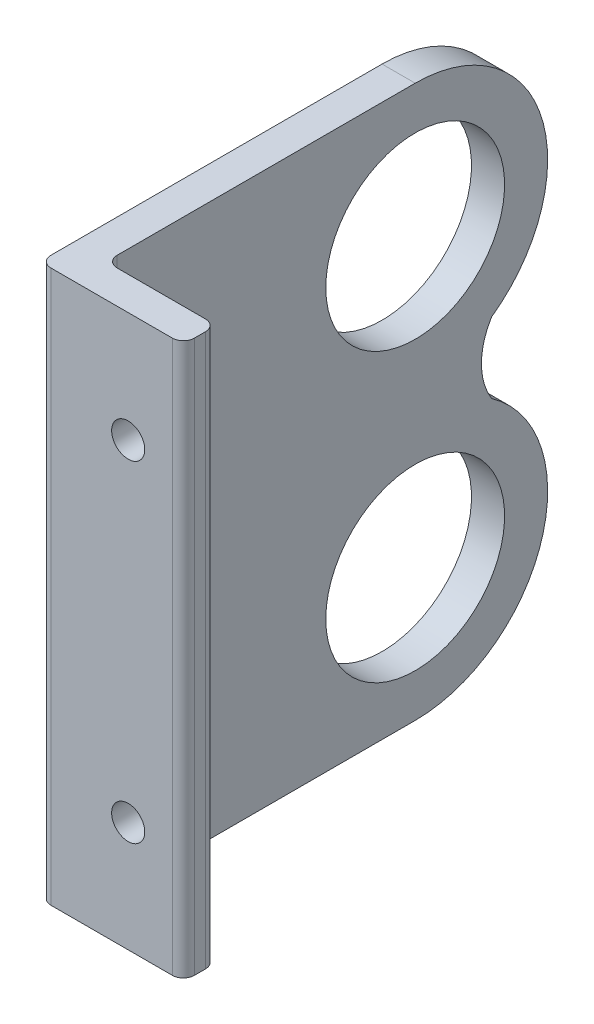
SolidWorks part; units mm, degrees
ref_plane "Front Plane" through (0, 0, 0) normal (0, 0, 1) x (1, 0, 0)
ref_plane "Top Plane" through (0, 0, 0) normal (0, 1, 0) x (1, 0, 0)
ref_plane "Right Plane" through (0, 0, 0) normal (1, 0, 0) x (0, 0, -1)
sketch "Sketch1" plane through (0, 0, 0) normal (0, 1, 0) x (1, 0, 0)
  line L1 (3.75, 31.3125) -> (6.75, 31.3125)
  line L2 (3.75, 31.3125) -> (3.75, -10.6875)
  line L3 (4.75, -11.6875) -> (6.75, -11.6875)
  line L4 (6.75, 31.3125) -> (6.75, -7.6875)
  line L5 (7.75, -8.6875) -> (15.75, -8.6875)
  line L6 (3.75, -8.6875) -> (3.75, -10.6875)
  line L7 (4.75, -11.6875) -> (15.75, -11.6875)
  line L8 (16.75, -9.6875) -> (16.75, -10.6875)
  arc A0 (16.75, -10.6875) -> (15.75, -11.6875) centre (15.75, -10.6875) cw
  arc A1 (15.75, -8.6875) -> (16.75, -9.6875) centre (15.75, -9.6875) cw
  arc A2 (7.75, -8.6875) -> (6.75, -7.6875) centre (7.75, -7.6875) cw
  arc A3 (3.75, -10.6875) -> (4.75, -11.6875) centre (4.75, -10.6875) ccw
  dimension "D2" = 1
extrude "Boss-Extrude1" add sketch "Sketch1" along normal blind 50 contours L8 L5 L4 L1 L2 L3 L7
sketch "Sketch2" plane through (0, 0, 11.6875) normal (0, 0, 1) x (1, 0, 0)
  line L0 (16.75, 50) -> (16.75, 0) construction
  line L1 (4.75, 50) -> (15.75, 50) construction
  line L2 (4.75, 0) -> (15.75, 0) construction
  circle A0 centre (11.75, 40) radius 1.5
  circle A1 centre (11.75, 10) radius 1.5
  dimension "D1" = 5
  dimension "D2" = 10
  dimension "D3" = 10
extrude "Cut-Extrude1" cut sketch "Sketch2" against normal blind 3
sketch "Sketch3" plane through (3.75, 0, 0) normal (-1, 0, 0) x (0, 0, 1)
  line L0 (11.6875, 50) -> (11.6875, 0) construction
  line L1 (-31.3125, 0) -> (10.6875, 0) construction
  line L2 (-31.3125, 50) -> (-31.3125, 0) construction
  line L4 (-19.3125, 0) -> (-31.3125, 0)
  line L5 (-31.3125, 0) -> (-31.3125, 12)
  line L6 (-31.3125, 50) -> (-19.3125, 50)
  line L7 (-31.3125, 38) -> (-31.3125, 50)
  circle A0 centre (-19.3125, 12) radius 8.1
  circle A1 centre (-19.3125, 38) radius 8.1
  arc A2 (-26.2365, 21.801) -> (-19.3125, 0) centre (-19.3125, 12) ccw
  arc A3 (-19.3125, 50) -> (-26.2365, 28.199) centre (-19.3125, 38) ccw
  arc A4 (-26.2365, 21.801) -> (-26.2365, 28.199) centre (-31.3125, 25) ccw
  point P6 (0, 0)
  point P21 (0, 0)
  dimension "D1" = 26
  dimension "D2" = 31
  dimension "D3" = 31
  dimension "D4" = 12
extrude "Cut-Extrude2" cut sketch "Sketch3" against normal blind 3
